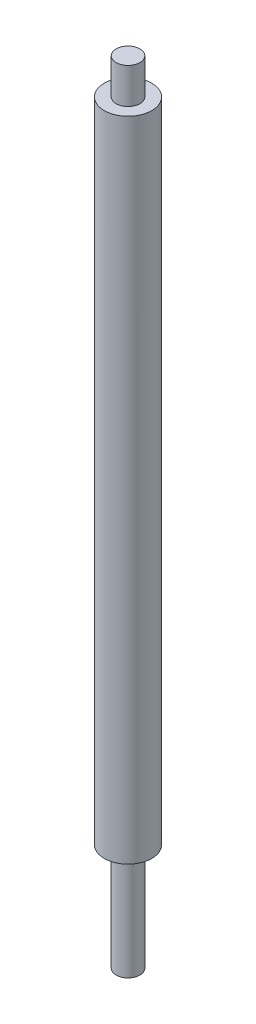
SolidWorks part; units mm, degrees
ref_plane "Front Plane" through (0, 0, 0) normal (0, 0, 1) x (1, 0, 0)
ref_plane "Top Plane" through (0, 0, 0) normal (0, 1, 0) x (1, 0, 0)
ref_plane "Right Plane" through (0, 0, 0) normal (1, 0, 0) x (0, 0, -1)
sketch "Sketch1" plane through (0, 0, 0) normal (0, 1, 0) x (1, 0, 0)
  circle A0 centre (0, 0) radius 6.35
  dimension "D1" = 12.7
extrude "Boss-Extrude1" add sketch "Sketch1" along normal blind 211.1375
sketch "Sketch2" plane through (0, 211.1375, 0) normal (0, 1, 0) x (1, 0, 0)
  circle A0 centre (0, 0) radius 3.175
  circle A1 centre (0, 0) radius 6.35
  dimension "D1" = 6.35
  dimension "D2" = 12.7
extrude "Cut-Extrude1" cut sketch "Sketch2" against normal blind 9.525
sketch "Sketch3" plane through (0, 0, 0) normal (0, -1, 0) x (1, 0, 0)
  circle A0 centre (0, 0) radius 6.35
  circle A1 centre (0, 0) radius 3.175
  dimension "D1" = 12.7
  dimension "D2" = 6.35
extrude "Cut-Extrude2" cut sketch "Sketch3" against normal blind 28.575
